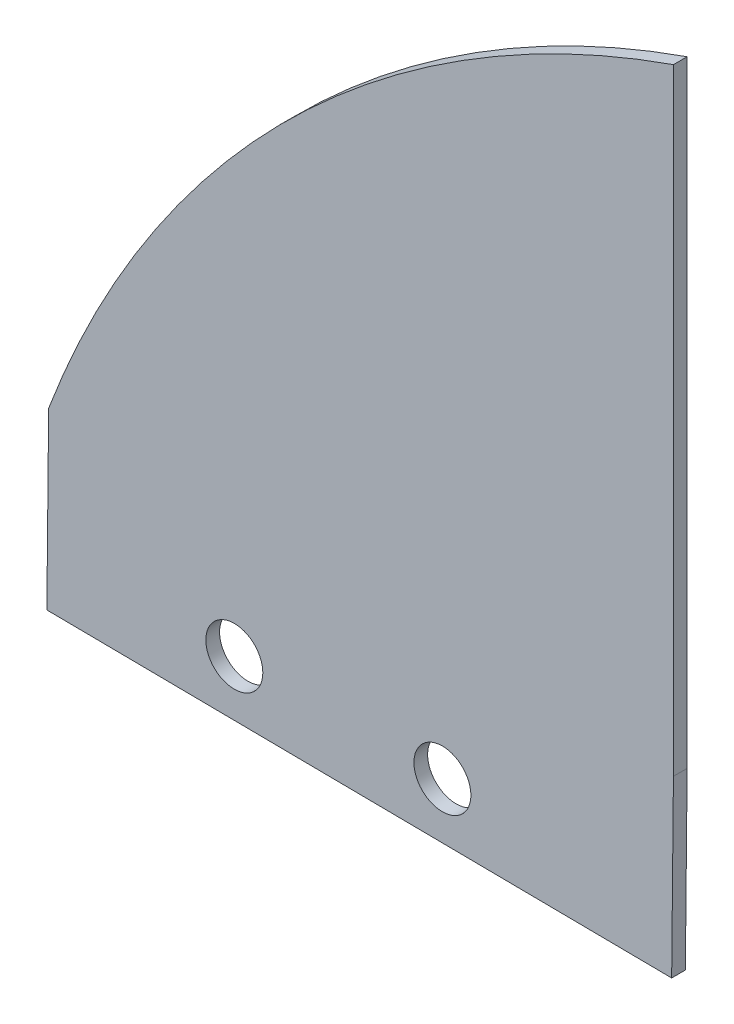
SolidWorks part; units mm, degrees
ref_plane "Front Plane" through (0, 0, 0) normal (0, 0, 1) x (1, 0, 0)
ref_plane "Top Plane" through (0, 0, 0) normal (0, 1, 0) x (1, 0, 0)
ref_plane "Right Plane" through (0, 0, 0) normal (1, 0, 0) x (0, 0, -1)
sketch "Sketch1" plane through (0, 0, 0) normal (0, 0, 1) x (1, 0, 0)
  line L8 (-68.8788, 27.1708) -> (-69.0845, 6.8333)
  line L9 (-69.0845, 6.8333) -> (3.29, 6.1012)
  line L10 (3.29, 6.1012) -> (3.4958, 26.4387)
  line L11 (3.4958, 26.4387) -> (3.4958, 97.8329)
  line L12 (-68.8788, 27.1708) -> (-69.0845, 6.8333)
  line L13 (-69.0845, 6.8333) -> (3.29, 6.1012)
  line L14 (3.29, 6.1012) -> (3.4958, 26.4387)
  line L15 (3.4958, 26.4387) -> (3.4958, 97.8329)
  circle A0 centre (-47.3681, 13.0425) radius 3.3 construction
  arc A1 (3.4958, 97.8329) -> (-68.8788, 27.1708) centre (42.8526, -14.873) ccw
  arc A2 (3.4958, 97.8329) -> (-68.8788, 27.1708) centre (42.8526, -14.873) ccw
  circle A3 centre (-23.2663, 12.7988) radius 3.3 construction
  circle A4 centre (-47.3681, 13.0425) radius 3.3
  circle A5 centre (-23.2663, 12.7988) radius 3.3
  dimension "D1" = 0
extrude "Boss-Extrude1" add sketch "Sketch1" along normal blind 1.5875 contours L15 A2 L12 L13 L14 A5 A4
